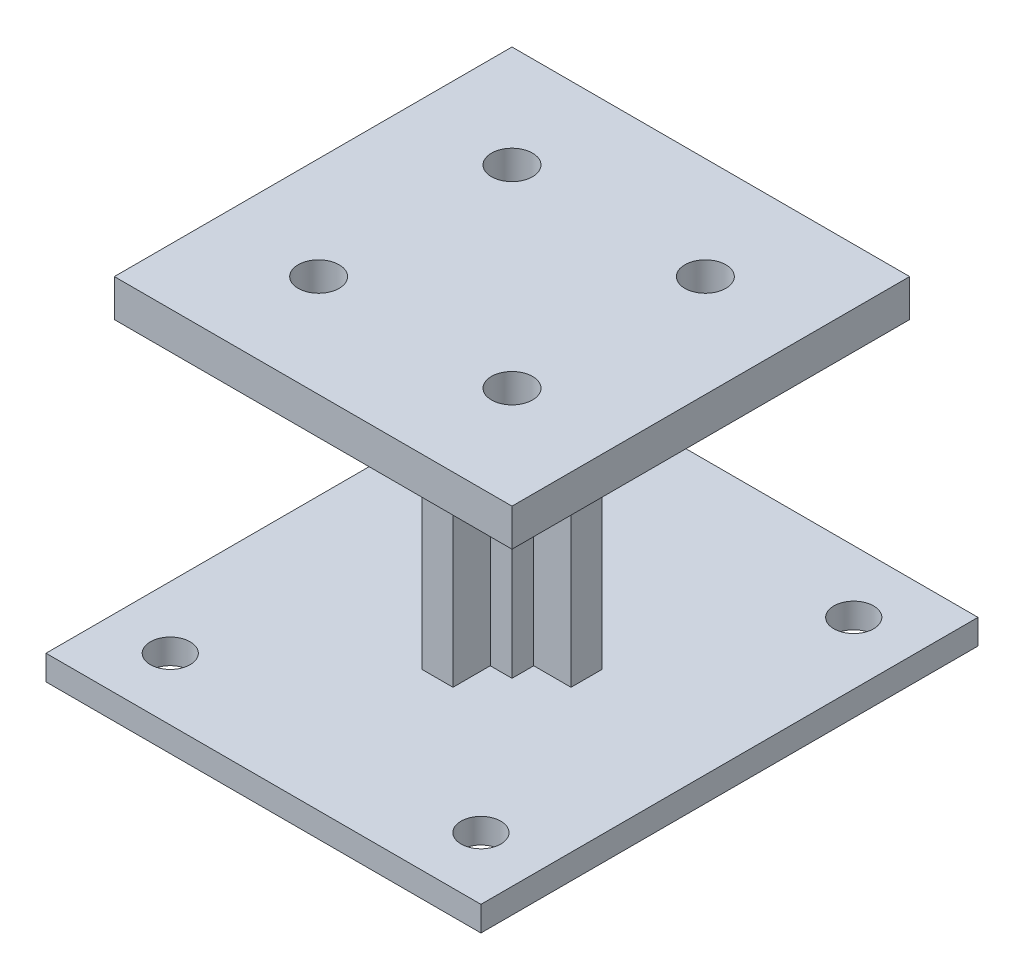
SolidWorks part; units mm, degrees
ref_plane "前视基准面" through (0, 0, 0) normal (0, 0, 1) x (1, 0, 0)
ref_plane "上视基准面" through (0, 0, 0) normal (0, 1, 0) x (1, 0, 0)
ref_plane "右视基准面" through (0, 0, 0) normal (1, 0, 0) x (0, 0, -1)
sketch "草图1" plane through (0, 0, 0) normal (0, 1, 0) x (1, 0, 0)
  line L1 (-17.5, -20) -> (17.5, -20)
  line L2 (-17.5, -20) -> (-17.5, 20)
  line L3 (-17.5, 20) -> (17.5, 20)
  line L4 (17.5, -20) -> (17.5, 20)
  line L5 (-17.5, -20) -> (17.5, 20) construction
  line L6 (-17.5, 20) -> (17.5, -20) construction
  point P0 (0, 0)
  dimension "D1" = 35
  dimension "D2" = 40
extrude "凸台-拉伸1" add sketch "草图1" along normal blind 2
sketch "草图2" plane through (0, 2, 0) normal (0, 1, 0) x (1, 0, 0)
  line L0 (0, -1.1) -> (0, 1.1) construction
  line L1 (-1.1, 0) -> (1.1, 0) construction
  circle A0 centre (-12.5, 15) radius 1.6
  circle A1 centre (12.5, 15) radius 1.6
  circle A2 centre (12.5, -15) radius 1.6
  circle A3 centre (-12.5, -15) radius 1.6
  dimension "D1" = 3.2
  dimension "D2" = 25
  dimension "D3" = 30
extrude "切除-拉伸1" cut sketch "草图2" against normal blind 2
sketch "草图3" plane through (0, 2, 0) normal (0, 1, 0) x (1, 0, 0)
  line L1 (-3, -3) -> (3, -3)
  line L2 (-3, -3) -> (-3, 3)
  line L3 (-3, 3) -> (3, 3)
  line L4 (3, -3) -> (3, 3)
  line L5 (-3, -3) -> (3, 3) construction
  line L6 (-3, 3) -> (3, -3) construction
  point P0 (0, 0)
  dimension "D1" = 6
  dimension "D2" = 6
extrude "凸台-拉伸2" add sketch "草图3" along normal blind 22
sketch "草图4" plane through (0, 24, 0) normal (0, 1, 0) x (1, 0, 0)
  line L1 (-16, -16) -> (16, -16)
  line L2 (-16, -16) -> (-16, 16)
  line L3 (-16, 16) -> (16, 16)
  line L4 (16, -16) -> (16, 16)
  line L5 (-16, -16) -> (16, 16) construction
  line L6 (-16, 16) -> (16, -16) construction
  line L7 (0, -13.2) -> (0, 13.2) construction
  line L8 (-13.2, 0) -> (13.2, 0) construction
  circle A0 centre (-7.78, 7.78) radius 1.65
  circle A1 centre (7.78, 7.78) radius 1.65
  circle A2 centre (7.78, -7.78) radius 1.65
  circle A3 centre (-7.78, -7.78) radius 1.65
  point P0 (0, 0)
  dimension "D1" = 3.3
  dimension "D2" = 15.56
  dimension "D3" = 15.56
  dimension "D4" = 32
  dimension "D5" = 32
extrude "凸台-拉伸3" add sketch "草图4" along normal blind 3
sketch "草图5" plane through (0, 0, 3) normal (0, 0, 1) x (1, 0, 0)
  line L0 (0, 24) -> (0, 2) construction
  line L1 (-1.25, 2) -> (1.25, 2)
  line L2 (-1.25, 2) -> (-1.25, 24)
  line L3 (-1.25, 24) -> (1.25, 24)
  line L4 (1.25, 2) -> (1.25, 24)
  line L5 (-1.25, 2) -> (1.25, 24) construction
  line L6 (-1.25, 24) -> (1.25, 2) construction
  line L7 (-3, 24) -> (3, 24) construction
  line L8 (-17.5, 2) -> (17.5, 2) construction
  line L9 (-3, 2) -> (3, 2) construction
  point P0 (0, 13)
  point P11 (0, 13)
  point P12 (1.4572, 2)
  dimension "D1" = 2.5
extrude "凸台-拉伸4" add sketch "草图5" along normal blind 3
pattern_circular "阵列(圆周)1" count 4 every 90 about axis through (0, 0, 0) along (0, 1, 0) of "凸台-拉伸4"
